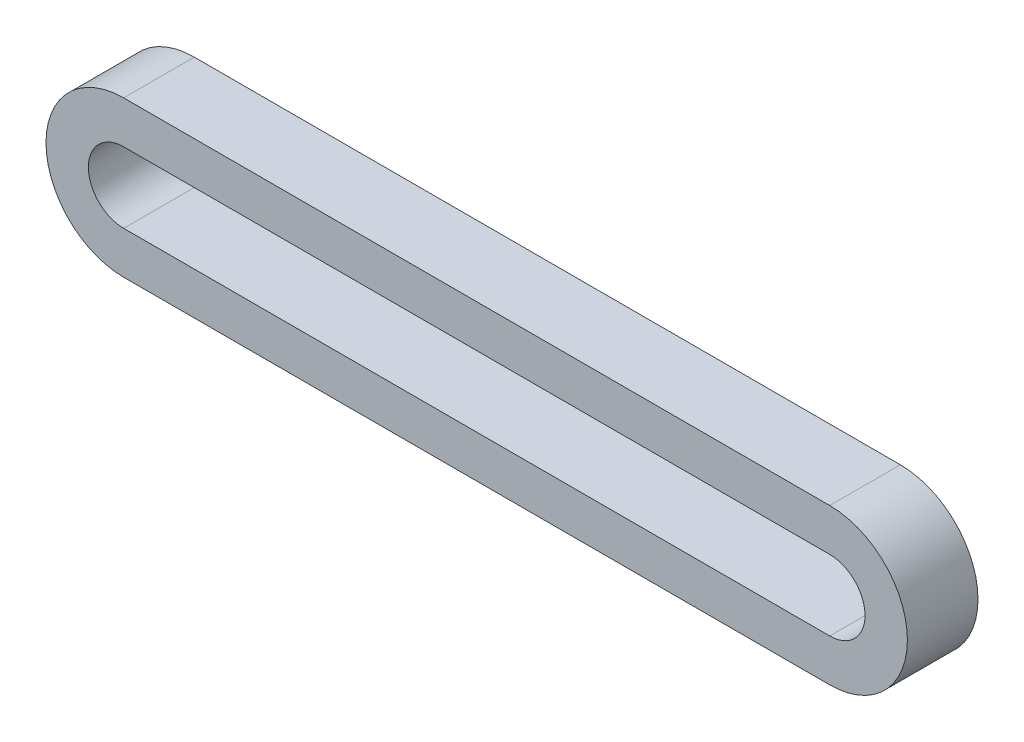
SolidWorks part; units mm, degrees
ref_plane "Front Plane" through (0, 0, 0) normal (0, 0, 1) x (1, 0, 0)
ref_plane "Top Plane" through (0, 0, 0) normal (0, 1, 0) x (1, 0, 0)
ref_plane "Right Plane" through (0, 0, 0) normal (1, 0, 0) x (0, 0, -1)
sketch "Sketch2" plane through (0, 0, 0) normal (0, 0, 1) x (1, 0, 0)
  line L0 (0, 0) -> (50, 0) construction
  line L1 (0, 2.5) -> (50, 2.5)
  line L2 (0, -2.5) -> (50, -2.5)
  line L3 (0, 5.5) -> (50, 5.5)
  line L4 (0, -5.5) -> (50, -5.5)
  arc A0 (0, 2.5) -> (0, -2.5) centre (0, 0) ccw
  arc A1 (50, -2.5) -> (50, 2.5) centre (50, 0) ccw
  arc A2 (50, -5.5) -> (50, 5.5) centre (50, 0) ccw
  arc A3 (0, 5.5) -> (0, -5.5) centre (0, 0) ccw
  point P3 (25, 0)
  dimension "D1" = 3
extrude "Boss-Extrude1" add sketch "Sketch2" along normal blind 5 contours L3 A3 L4 A2 A1 L2 A0 L1
